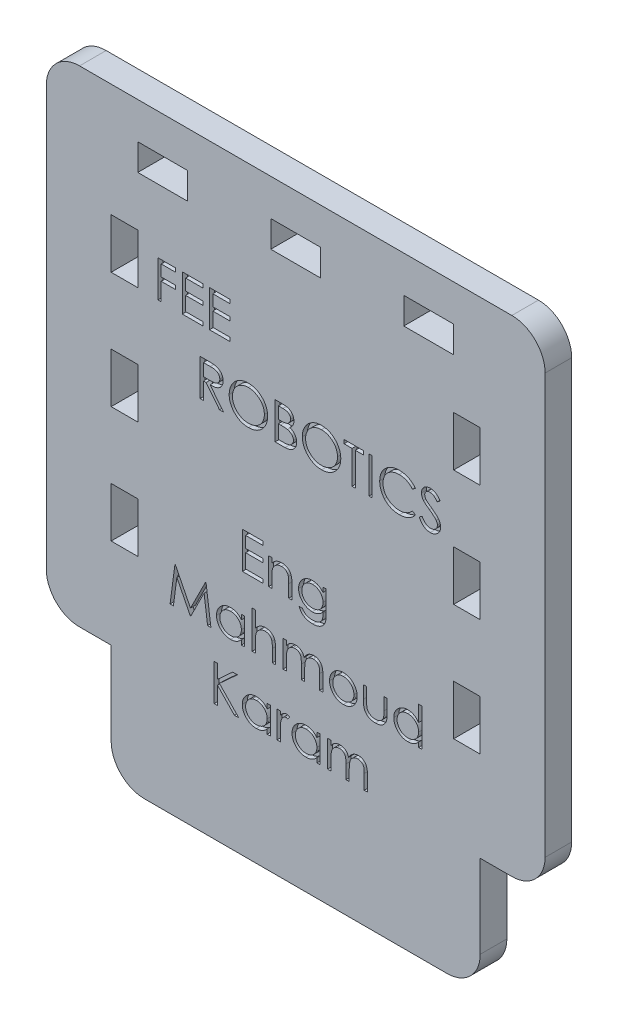
SolidWorks part; units mm, degrees
material "Beech"
ref_plane "Front" through (0, 0, 0) normal (0, 0, 1) x (1, 0, 0)
ref_plane "Top" through (0, 0, 0) normal (0, 1, 0) x (1, 0, 0)
ref_plane "Right" through (0, 0, 0) normal (1, 0, 0) x (0, 0, -1)
sketch "Sketch1" plane through (0, 0, 0) normal (0, 0, 1) x (1, 0, 0)
  line L0 (75, -55.5626) -> (-75, -55.5626) construction
  line L1 (-75, -90.5626) -> (75, -90.5626) construction
  line L2 (-75, -90.5626) -> (-75, 90.5626) construction
  line L3 (-75, 90.5626) -> (75, 90.5626) construction
  line L4 (75, -90.5626) -> (75, 90.5626) construction
  line L5 (-75, -90.5626) -> (75, 90.5626) construction
  line L6 (-75, 90.5626) -> (75, -90.5626) construction
  line L7 (-65, 90.5626) -> (65, 90.5626)
  line L8 (45.5, -90.5626) -> (-45.5, -90.5626)
  line L9 (75, -45.5626) -> (75, 80.5626) construction
  line L10 (65, 90.5626) -> (-65, 90.5626) construction
  line L12 (-55.5, -90.5626) -> (45.5, -90.5626) construction
  line L13 (-65, -55.5626) -> (-55.5, -55.5626)
  line L14 (-55.5, -55.5626) -> (-55.5, -80.5626)
  line L15 (0, 20.9251) -> (0, -23.2115) construction
  line L16 (55.5, -55.5626) -> (55.5, -80.5626)
  line L17 (75, 80.5626) -> (75, -45.5626)
  line L18 (65, -55.5626) -> (55.5, -55.5626)
  line L19 (7.5, 71.5626) -> (-7.5, 71.5626)
  line L20 (-75, -45.5626) -> (-75, 80.5626)
  line L21 (-47.5, 79.5626) -> (-32.5, 79.5626)
  line L22 (-47.5, 79.5626) -> (-47.5, 71.5626)
  line L23 (-47.5, 71.5626) -> (-32.5, 71.5626)
  line L24 (-32.5, 79.5626) -> (-32.5, 71.5626)
  line L25 (-47.5, 79.5626) -> (-32.5, 71.5626) construction
  line L26 (-47.5, 71.5626) -> (-32.5, 79.5626) construction
  line L27 (-7.5, 71.5626) -> (-7.5, 79.5626)
  line L28 (-7.5, 79.5626) -> (7.5, 79.5626)
  line L29 (0, 79.5626) -> (0, 71.5626) construction
  line L30 (47.5, 79.5626) -> (32.5, 79.5626)
  line L31 (47.5, 79.5626) -> (47.5, 71.5626)
  line L32 (47.5, 71.5626) -> (32.5, 71.5626)
  line L33 (32.5, 79.5626) -> (32.5, 71.5626)
  line L34 (7.5, 71.5626) -> (7.5, 79.5626)
  line L35 (0, -14.0626) -> (0, -1.3036) construction
  line L36 (-47.5, 56.5626) -> (-55.5, 56.5626)
  line L37 (-47.5, 56.5626) -> (-47.5, 41.5626)
  line L38 (-47.5, 41.5626) -> (-55.5, 41.5626)
  line L39 (-55.5, 56.5626) -> (-55.5, 41.5626)
  line L40 (-47.5, 56.5626) -> (-55.5, 41.5626) construction
  line L41 (-47.5, 41.5626) -> (-55.5, 56.5626) construction
  line L42 (-47.5, 6.5626) -> (-55.5, 6.5626)
  line L43 (-55.5, 21.5626) -> (-55.5, 6.5626)
  line L44 (-47.5, 21.5626) -> (-55.5, 21.5626)
  line L45 (-47.5, 21.5626) -> (-47.5, 6.5626)
  line L46 (-47.5, -28.4374) -> (-55.5, -28.4374)
  line L47 (-55.5, -13.4374) -> (-55.5, -28.4374)
  line L48 (-47.5, -13.4374) -> (-55.5, -13.4374)
  line L49 (-47.5, -13.4374) -> (-47.5, -28.4374)
  line L50 (47.5, 41.5626) -> (55.5, 41.5626)
  line L51 (55.5, 56.5626) -> (55.5, 41.5626)
  line L52 (47.5, 56.5626) -> (55.5, 56.5626)
  line L53 (47.5, 56.5626) -> (47.5, 41.5626)
  line L54 (47.5, -13.4374) -> (47.5, -28.4374)
  line L55 (47.5, -13.4374) -> (55.5, -13.4374)
  line L56 (55.5, -13.4374) -> (55.5, -28.4374)
  line L57 (47.5, -28.4374) -> (55.5, -28.4374)
  line L58 (47.5, 21.5626) -> (47.5, 6.5626)
  line L59 (47.5, 21.5626) -> (55.5, 21.5626)
  line L60 (55.5, 21.5626) -> (55.5, 6.5626)
  line L61 (47.5, 6.5626) -> (55.5, 6.5626)
  arc A5 (75, 80.5626) -> (65, 90.5626) centre (65, 80.5626) ccw
  arc A6 (-65, 90.5626) -> (-75, 80.5626) centre (-65, 80.5626) ccw
  arc A8 (-45.5, -90.5626) -> (-55.5, -80.5626) centre (-45.5, -80.5626) cw
  arc A10 (-75, -45.5626) -> (-65, -55.5626) centre (-65, -45.5626) ccw
  arc A11 (45.5, -90.5626) -> (55.5, -80.5626) centre (45.5, -80.5626) ccw
  arc A13 (75, -45.5626) -> (65, -55.5626) centre (65, -45.5626) cw
  point P0 (0, 0)
  point P8 (0, 0)
  point P9 (0, 0)
  point P12 (0, 0)
  point P16 (0, 0)
  point P18 (-55.5, -55.5626)
  point P30 (0, 0)
  point P33 (0, 0)
  point P34 (0, 0)
  point P37 (0, 0)
  point P38 (0, 0)
  point P39 (0, 0)
  point P40 (0, 0)
  point P41 (0, 0)
  point P46 (-40, 75.5626)
  point P61 (-51.5, 49.0626)
  point P84 (-51.5, 6.5626)
  point P85 (0, 0)
  dimension "D6" = 19.5
  dimension "D7" = 181.1252
  dimension "D8" = 15
  dimension "D11" = 25
  dimension "D14" = 15
  dimension "D5" = 10
  dimension "D3" = 10
  dimension "D1" = 126.1252
  dimension "D2" = 150
  dimension "D4" = 35
  dimension "D9" = 8
  dimension "D10" = 7.5
  dimension "D12" = 11
  dimension "D13" = 8
  dimension "D15" = 20
  dimension "D16" = 15
  dimension "D17" = 20
extrude "Boss-Extrude1" add sketch "Sketch1" along normal blind 8
sketch "Sketch2" plane through (0, 0, 8) normal (0, 0, 1) x (1, 0, 0)
  text T0 "FEE\r\n   ROBOTICS\r\n \r\n      Eng\r\n Mahmoud\r\n    Karam" font "Century Gothic" height 11
extrude "Cut-Extrude1" cut sketch "Sketch2" against normal blind 1.5
